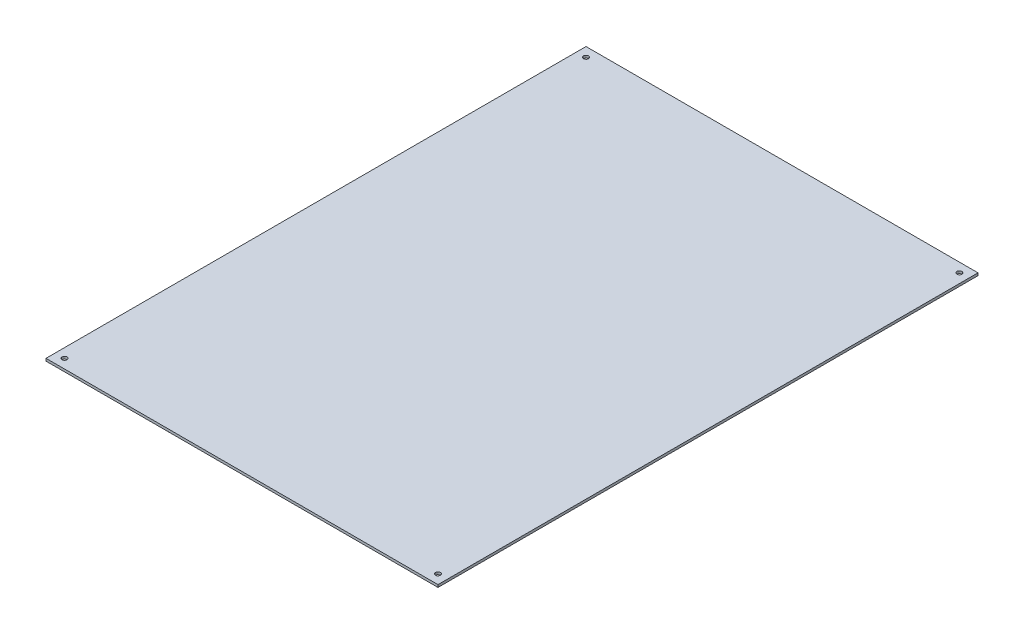
SolidWorks part; units mm, degrees
ref_plane "Front Plane" through (0, 0, 0) normal (0, 0, 1) x (1, 0, 0)
ref_plane "Top Plane" through (0, 0, 0) normal (0, 1, 0) x (1, 0, 0)
ref_plane "Right Plane" through (0, 0, 0) normal (1, 0, 0) x (0, 0, -1)
sketch "Sketch1" plane through (0, 0, 0) normal (1, 0, 0) x (0, 0, -1)
  line L2 (0, 0) -> (435, 0)
  line L3 (0, 0) -> (0, 2)
  line L4 (0, 2) -> (435, 2)
  line L5 (435, 0) -> (435, 2)
  dimension "D1" = 2
  dimension "D2" = 435
extrude "Boss-Extrude1" add sketch "Sketch1" along normal blind 157.875
sketch "Sketch3" plane through (0, 2, 0) normal (0, 1, 0) x (1, 0, 0)
  line L0 (157.875, 435) -> (157.875, 0) construction
  line L1 (157.875, 435) -> (0, 435) construction
  line L2 (-55, 0) -> (55, 0) construction
  circle A0 centre (150.375, 427.5) radius 2
  circle A1 centre (150.375, 7.5) radius 2
  dimension "D1" = 7.5
  dimension "D3" = 7.5
  dimension "D2" = 7.5
  dimension "D4" = 7.5
extrude "Cut-Extrude1" cut sketch "Sketch3" along direction (0, 1, 0) on the side against the normal up to next (2 mm away)
mirror "Mirror1" about plane through (0, 0, 0) normal (1, 0, 0) of "Cut-Extrude1", "Boss-Extrude1"
